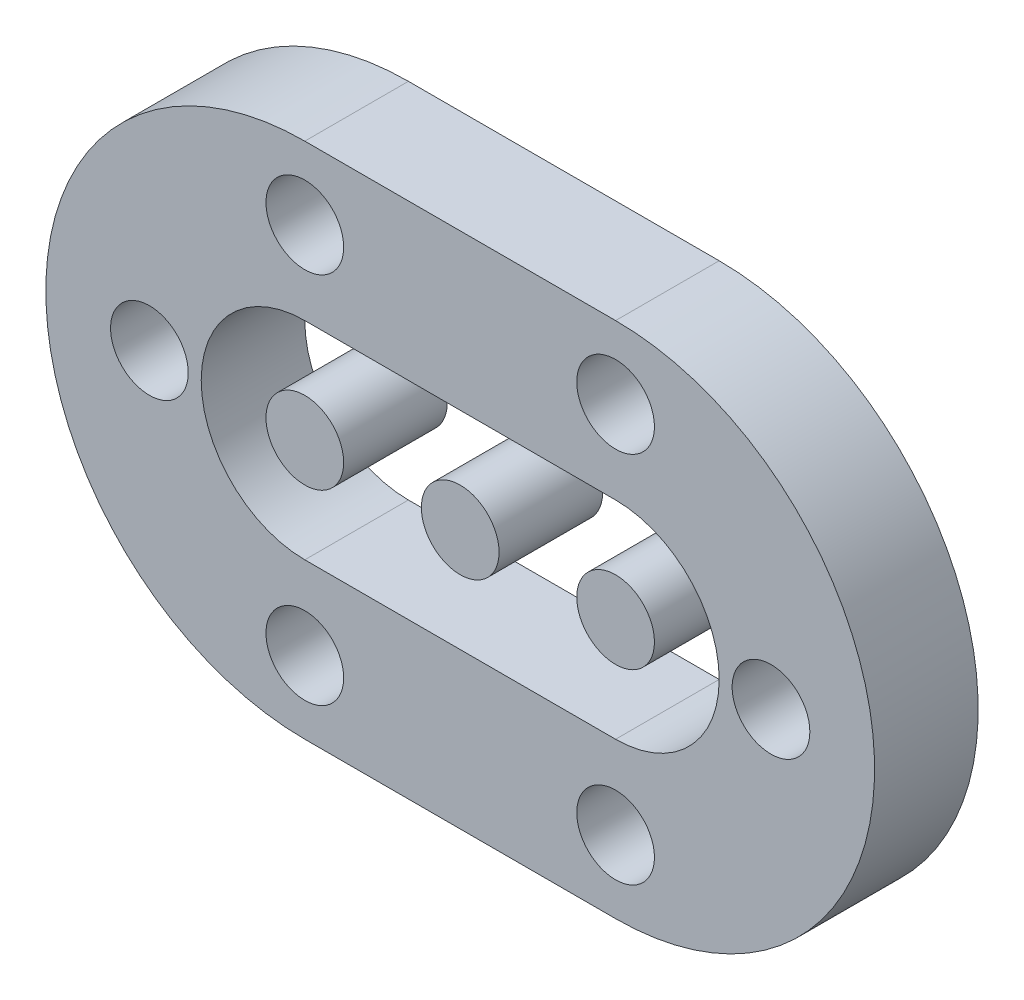
SolidWorks part; units mm, degrees
ref_plane "Alzado" through (0, 0, 0) normal (0, 0, 1) x (1, 0, 0)
ref_plane "Planta" through (0, 0, 0) normal (0, 1, 0) x (1, 0, 0)
ref_plane "Vista lateral" through (0, 0, 0) normal (1, 0, 0) x (0, 0, -1)
sketch "Croquis1" plane through (0, 0, 0) normal (0, 0, 1) x (1, 0, 0)
  line L0 (0, 0) -> (-30, 0) construction
  line L1 (0, -10) -> (-30, -10)
  line L2 (0, 10) -> (-30, 10)
  line L3 (0, -25) -> (-30, -25)
  line L4 (0, 25) -> (-30, 25)
  line L5 (-45, 0) -> (-30, 0) construction
  line L6 (-30, 0) -> (-30, 18) construction
  line L7 (-30, 0) -> (-30, -18) construction
  arc A0 (0, -10) -> (0, 10) centre (0, 0) ccw
  arc A1 (-30, 10) -> (-30, -10) centre (-30, 0) ccw
  arc A2 (-30, 25) -> (-30, -25) centre (-30, 0) ccw
  arc A3 (0, -25) -> (0, 25) centre (0, 0) ccw
  circle A4 centre (-45, 0) radius 3.75
  circle A5 centre (-30, 0) radius 3.75
  circle A6 centre (-15, 0) radius 3.75
  circle A7 centre (0, 0) radius 3.75
  circle A8 centre (15, 0) radius 3.75
  circle A9 centre (-30, 18) radius 3.75
  circle A10 centre (0, 18) radius 3.75
  circle A11 centre (-30, -18) radius 3.75
  circle A12 centre (0, -18) radius 3.75
  point P3 (-15, 0)
  dimension "D4" = 7.5
  dimension "D2" = 20
  dimension "D3" = 30
  dimension "D5" = 15
  dimension "D7" = 15
  dimension "D9" = 18
  dimension "D11" = 18
  dimension "D1" = 15
  dimension "D6" = 5
  dimension "D8" = 2
  dimension "D10" = 2
extrude "Saliente-Extruir1" add sketch "Croquis1" along normal blind 10 contours L3 A3 L4 A2 A12 A11 A10 A9 A8 A4 A1 L2 A0 L1 | A5 | A7 | A6
